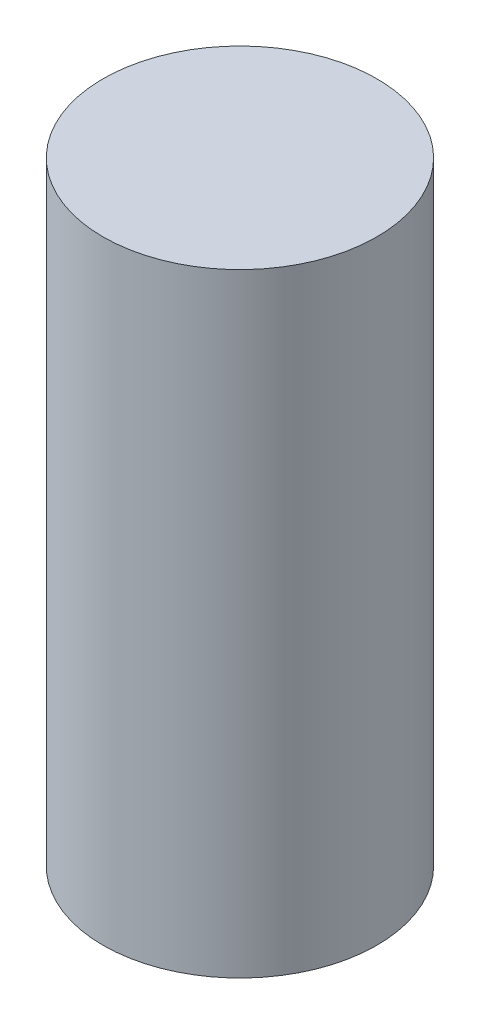
SolidWorks part; units mm, degrees
ref_plane "Front Plane" through (0, 0, 0) normal (0, 0, 1) x (1, 0, 0)
ref_plane "Top Plane" through (0, 0, 0) normal (0, 1, 0) x (1, 0, 0)
ref_plane "Right Plane" through (0, 0, 0) normal (1, 0, 0) x (0, 0, -1)
sketch "Sketch1" plane through (0, 0, 0) normal (0, 1, 0) x (1, 0, 0)
  circle A0 centre (0, 0) radius 31.25
  dimension "D1" = 62.5
extrude "Boss-Extrude1" add sketch "Sketch1" along normal blind 140
